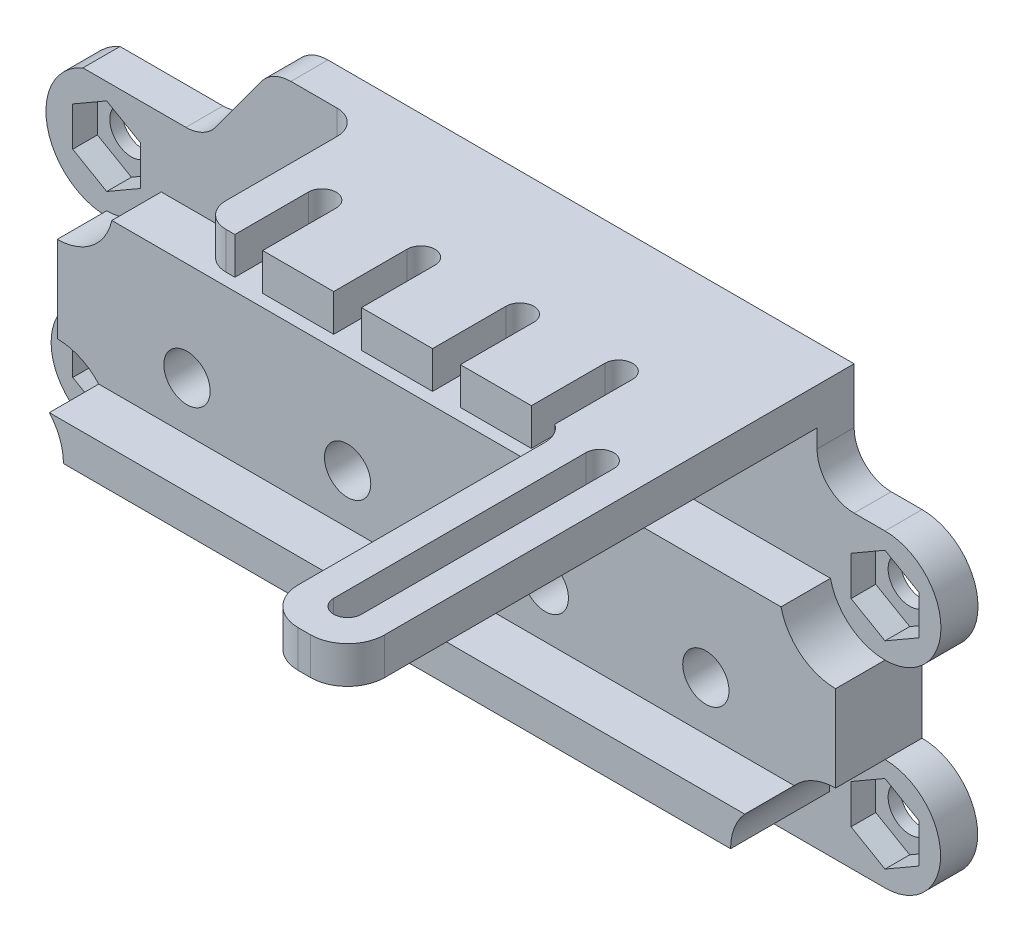
SolidWorks part; units mm, degrees
ref_plane "Plan de face" through (0, 0, 0) normal (0, 0, 1) x (1, 0, 0)
ref_plane "Plan de dessus" through (0, 0, 0) normal (0, 1, 0) x (1, 0, 0)
ref_plane "Plan de droite" through (0, 0, 0) normal (1, 0, 0) x (0, 0, -1)
sketch "Esquisse1" plane through (0, 0, 0) normal (0, 0, 1) x (1, 0, 0)
  line L0 (-12.7078, -15.9074) -> (13.2922, -15.9074) construction
  line L1 (-33.1328, 9.1203) -> (-23.2721, 9.1203)
  line L2 (31.7922, 0.0649) -> (31.7922, -6.9074)
  line L3 (-31.2078, -15.9074) -> (31.7922, -15.9074)
  line L4 (26.2922, 9.1203) -> (26.2922, 16.5903)
  line L5 (31.7922, 0.0649) -> (31.7922, -6.8797) construction
  line L7 (-31.2078, -0.3273) -> (-31.2078, -6.9074)
  line L8 (26.2922, 16.5903) -> (-17.8244, 16.5903)
  line L10 (-17.8244, 16.5903) -> (-23.2721, 9.1203)
  line L11 (26.2922, 9.1203) -> (31.7922, 9.1203)
  arc A0 (-33.1328, 9.1203) -> (-31.2078, -0.3273) centre (-31.2078, 4.5926) ccw
  arc A1 (-31.2078, -6.9074) -> (-31.2078, -15.9074) centre (-31.2078, -11.4074) ccw
  arc A2 (31.7922, 0.0649) -> (31.7922, 9.1203) centre (31.7922, 4.5926) ccw
  arc A3 (31.7922, -15.9074) -> (31.7922, -6.9074) centre (31.7922, -11.4074) ccw
  circle A4 centre (-31.2078, 4.5926) radius 1.75
  circle A5 centre (-31.2078, -11.4074) radius 1.75
  circle A6 centre (31.7922, 4.5926) radius 1.75
  circle A7 centre (31.7922, -11.4074) radius 1.75
  dimension "D1" = 7.47
  dimension "D2" = 5.5
extrude "Boss.-Extru.1" add sketch "Esquisse1" along normal blind 3
sketch "Esquisse2" plane through (0, 0, 3) normal (0, 0, 1) x (1, 0, 0)
  line L1 (-28.4578, 6.1803) -> (-31.2078, 7.768)
  line L2 (-31.2078, 7.768) -> (-33.9578, 6.1803)
  line L3 (-33.9578, 6.1803) -> (-33.9578, 3.0049)
  line L4 (-33.9578, 3.0049) -> (-31.2078, 1.4172)
  line L5 (-31.2078, 1.4172) -> (-28.4578, 3.0049)
  line L6 (-28.4578, 3.0049) -> (-28.4578, 6.1803)
  line L7 (-28.4578, -9.8197) -> (-31.2078, -8.232)
  line L8 (-31.2078, -8.232) -> (-33.9578, -9.8197)
  line L9 (-33.9578, -9.8197) -> (-33.9578, -12.9951)
  line L10 (-33.9578, -12.9951) -> (-31.2078, -14.5828)
  line L11 (-31.2078, -14.5828) -> (-28.4578, -12.9951)
  line L12 (-28.4578, -12.9951) -> (-28.4578, -9.8197)
  line L13 (29.0422, -9.8197) -> (29.0422, -12.9951)
  line L14 (29.0422, -12.9951) -> (31.7922, -14.5828)
  line L15 (31.7922, -14.5828) -> (34.5422, -12.9951)
  line L16 (34.5422, -12.9951) -> (34.5422, -9.8197)
  line L17 (34.5422, -9.8197) -> (31.7922, -8.232)
  line L18 (31.7922, -8.232) -> (29.0422, -9.8197)
  line L19 (29.0422, 3.0049) -> (31.7922, 1.4172)
  line L20 (31.7922, 1.4172) -> (34.5422, 3.0049)
  line L21 (34.5422, 3.0049) -> (34.5422, 6.1803)
  line L22 (34.5422, 6.1803) -> (31.7922, 7.768)
  line L23 (31.7922, 7.768) -> (29.0422, 6.1803)
  line L24 (29.0422, 6.1803) -> (29.0422, 3.0049)
  circle A0 centre (-31.2078, 4.5926) radius 2.75 construction
  circle A1 centre (-31.2078, -11.4074) radius 2.75 construction
  circle A2 centre (31.7922, -11.4074) radius 2.75 construction
  circle A3 centre (31.7922, 4.5926) radius 2.75 construction
  dimension "D1" = 5.5
  dimension "D2" = 5.5
  dimension "D3" = 5.5
  dimension "D4" = 5.5
extrude "Enlèv. mat.-Extru.1" cut sketch "Esquisse2" against normal blind 2
sketch "Esquisse3" plane through (0, 0, 3) normal (0, 0, 1) x (1, 0, 0)
  line L0 (-31.2078, -0.3273) -> (-31.2078, -6.9074) construction
  line L1 (-31.2078, 3.5926) -> (31.7922, 3.5926)
  line L2 (-31.2078, 3.5926) -> (-31.2078, -11.4074)
  line L3 (-31.2078, -11.4074) -> (31.7922, -11.4074)
  line L4 (31.7922, 3.5926) -> (31.7922, -11.4074)
  line L5 (31.7922, -6.9074) -> (31.7922, 0.0649) construction
  dimension "D1" = 15
extrude "Boss.-Extru.2" add sketch "Esquisse3" along normal blind 4
sketch "Esquisse5" plane through (0, 0, 7) normal (0, 0, 1) x (1, 0, 0)
  line L0 (-31.2078, 3.5926) -> (-31.2078, -11.4074) construction
  line L1 (-31.2078, -8.4074) -> (31.7922, -8.4074)
  line L2 (-31.2078, -8.4074) -> (-31.2078, -11.4074)
  line L3 (-31.2078, -11.4074) -> (31.7922, -11.4074)
  line L4 (31.7922, -8.4074) -> (31.7922, -11.4074)
  dimension "D1" = 3
extrude "Boss.-Extru.3" add sketch "Esquisse5" along normal blind 4
sketch "Esquisse4" plane through (0, 0, 3) normal (0, 0, 1) x (1, 0, 0)
  circle A0 centre (-31.2078, -11.4074) radius 4.5
  circle A1 centre (31.7922, -11.4074) radius 4.5
  circle A2 centre (-31.2078, 4.5926) radius 4.5277
  circle A3 centre (31.7922, 4.5926) radius 4.5277
extrude "Enlèv. mat.-Extru.2" cut sketch "Esquisse4" along normal through all
sketch "Esquisse6" plane through (0, 0, 7) normal (0, 0, 1) x (1, 0, 0)
  line L0 (-31.2078, -4.4074) -> (31.7922, -4.4074) construction
  line L1 (28.4381, -8.4074) -> (-27.8537, -8.4074) construction
  line L2 (31.7922, -6.9074) -> (31.7922, 0.0649) construction
  line L3 (-31.2078, 0.0649) -> (-31.2078, -6.9074) construction
  line L4 (0.2922, -4.4074) -> (0.2922, -34.9823) construction
  circle A0 centre (-20.7078, -4.4074) radius 1.875
  circle A1 centre (-7.7078, -4.4074) radius 1.875
  dimension "D2" = 3.75
  dimension "D4" = 3.75
  dimension "D1" = 4
  dimension "D3" = 21
  dimension "D5" = 8
extrude "Enlèv. mat.-Extru.4" cut sketch "Esquisse6" against normal through all
sketch "Esquisse7" plane through (0, 0, 0) normal (0, 0, -1) x (-1, 0, 0)
  line L1 (23.4578, -2.8197) -> (20.7078, -1.232)
  line L2 (20.7078, -1.232) -> (17.9578, -2.8197)
  line L3 (17.9578, -2.8197) -> (17.9578, -5.9951)
  line L4 (17.9578, -5.9951) -> (20.7078, -7.5828)
  line L5 (20.7078, -7.5828) -> (23.4578, -5.9951)
  line L6 (23.4578, -5.9951) -> (23.4578, -2.8197)
  line L7 (10.4578, -2.8197) -> (7.7078, -1.232)
  line L8 (7.7078, -1.232) -> (4.9578, -2.8197)
  line L9 (4.9578, -2.8197) -> (4.9578, -5.9951)
  line L10 (4.9578, -5.9951) -> (7.7078, -7.5828)
  line L11 (7.7078, -7.5828) -> (10.4578, -5.9951)
  line L12 (10.4578, -5.9951) -> (10.4578, -2.8197)
  circle A0 centre (20.7078, -4.4074) radius 2.75 construction
  circle A1 centre (7.7078, -4.4074) radius 2.75 construction
  dimension "D1" = 5.5
  dimension "D2" = 5.5
extrude "Enlèv. mat.-Extru.5" cut sketch "Esquisse7" against normal blind 4
ref_plane "Plan1" through (0.2922, 0, 0) normal (1, 0, 0) x (0, 0, -1)
mirror "Symétrie1" about plane through (0.2922, 0, 0) normal (1, 0, 0) of "Enlèv. mat.-Extru.5", "Enlèv. mat.-Extru.4"
sketch "Esquisse8" plane through (0, 0, 3) normal (0, 0, 1) x (1, 0, 0)
  line L0 (26.2922, 9.1203) -> (26.2922, 16.5903) construction
  line L1 (26.2922, 16.5903) -> (-10.5669, 16.5903)
  line L2 (26.2922, 16.5903) -> (26.2922, 13.5903)
  line L3 (26.2922, 13.5903) -> (-10.5669, 13.5903)
  line L4 (-10.5669, 16.5903) -> (-10.5669, 13.5903)
  line L5 (26.2922, 16.5903) -> (-17.8244, 16.5903) construction
  dimension "D1" = 3
extrude "Boss.-Extru.4" add sketch "Esquisse8" along normal blind 13
fillet "Congé1" radius 3 3 edges at (-23.2721, 9.1203, 1.5) (26.2922, 9.1203, 1.5) (-17.8244, 16.5903, 1.5)
sketch "Esquisse9" plane through (0, 0, 16) normal (0, 0, 1) x (1, 0, 0)
  line L0 (-10.5669, 13.5903) -> (26.2922, 13.5903) construction
  line L1 (26.2922, 16.5903) -> (19.2922, 16.5903)
  line L2 (26.2922, 16.5903) -> (26.2922, 13.5903)
  line L3 (26.2922, 13.5903) -> (19.2922, 13.5903)
  line L4 (19.2922, 16.5903) -> (19.2922, 13.5903)
  dimension "D1" = 7
extrude "Boss.-Extru.5" add sketch "Esquisse9" along normal blind 25
fillet "Congé2" radius 3 2 edges at (19.2922, 15.0903, 41) (26.2922, 15.0903, 41)
fillet "Congé3" radius 2 1 edges
fillet "Congé4" radius 2 2 edges at (-10.5669, 15.0903, 3) (-10.5669, 15.0903, 16)
sketch "Esquisse10" plane through (0, 13.5903, 0) normal (0, -1, 0) x (1, 0, 0)
  line L0 (22.7922, 41) -> (22.7922, 13.4299) construction
  line L1 (22.2922, 41) -> (23.2922, 41) construction
  line L2 (22.7922, 37.5) -> (22.7922, 17.0885) construction
  line L3 (23.9172, 37.5) -> (23.9172, 17.0885)
  line L4 (21.6672, 37.5) -> (21.6672, 17.0885)
  line L7 (17.2922, 13.5) -> (17.2922, 6.6163) construction
  line L8 (9.2922, 13.5) -> (9.2922, 6.6163) construction
  line L9 (1.2922, 13.5) -> (1.2922, 6.6163) construction
  line L10 (-6.7078, 13.5) -> (-6.7078, 6.6163) construction
  line L11 (17.2922, 13.5) -> (17.2922, 23.2129) construction
  line L12 (9.2922, 13.5) -> (9.2922, 23.2129) construction
  line L13 (1.2922, 13.5) -> (1.2922, 23.2129) construction
  line L14 (-6.7078, 13.5) -> (-6.7078, 23.2129) construction
  line L15 (17.2922, 23.2129) -> (17.2922, 10.0582) construction
  line L16 (18.4172, 23.2129) -> (18.4172, 10.0582)
  line L17 (16.1672, 23.2129) -> (16.1672, 10.0582)
  line L18 (9.2922, 23.2129) -> (9.2922, 10.0582) construction
  line L19 (10.4172, 23.2129) -> (10.4172, 10.0582)
  line L20 (8.1672, 23.2129) -> (8.1672, 10.0582)
  line L21 (1.2922, 23.2129) -> (1.2922, 10.0582) construction
  line L22 (2.4172, 23.2129) -> (2.4172, 10.0582)
  line L23 (0.1672, 23.2129) -> (0.1672, 10.0582)
  line L24 (-6.7078, 23.2129) -> (-6.7078, 10.0582) construction
  line L25 (-5.5828, 23.2129) -> (-5.5828, 10.0582)
  line L26 (-7.8328, 23.2129) -> (-7.8328, 10.0582)
  arc A0 (23.9172, 37.5) -> (21.6672, 37.5) centre (22.7922, 37.5) ccw
  arc A1 (21.6672, 17.0885) -> (23.9172, 17.0885) centre (22.7922, 17.0885) ccw
  arc A2 (18.4172, 23.2129) -> (16.1672, 23.2129) centre (17.2922, 23.2129) ccw
  arc A3 (16.1672, 10.0582) -> (18.4172, 10.0582) centre (17.2922, 10.0582) ccw
  arc A4 (10.4172, 23.2129) -> (8.1672, 23.2129) centre (9.2922, 23.2129) ccw
  arc A5 (8.1672, 10.0582) -> (10.4172, 10.0582) centre (9.2922, 10.0582) ccw
  arc A6 (2.4172, 23.2129) -> (0.1672, 23.2129) centre (1.2922, 23.2129) ccw
  arc A7 (0.1672, 10.0582) -> (2.4172, 10.0582) centre (1.2922, 10.0582) ccw
  arc A8 (-5.5828, 23.2129) -> (-7.8328, 23.2129) centre (-6.7078, 23.2129) ccw
  arc A9 (-7.8328, 10.0582) -> (-5.5828, 10.0582) centre (-6.7078, 10.0582) ccw
  point P6 (22.7922, 27.2942)
  point P25 (17.2922, 16.6355)
  point P34 (9.2922, 16.6355)
  point P39 (1.2922, 16.6355)
  point P45 (-6.7078, 16.6355)
  dimension "D1" = 2.25
  dimension "D2" = 3.5
  dimension "D3" = 2.25
  dimension "D4" = 2.25
  dimension "D5" = 2.25
  dimension "D6" = 2.25
extrude "Enlèv. mat.-Extru.6" cut sketch "Esquisse10" against normal through all
